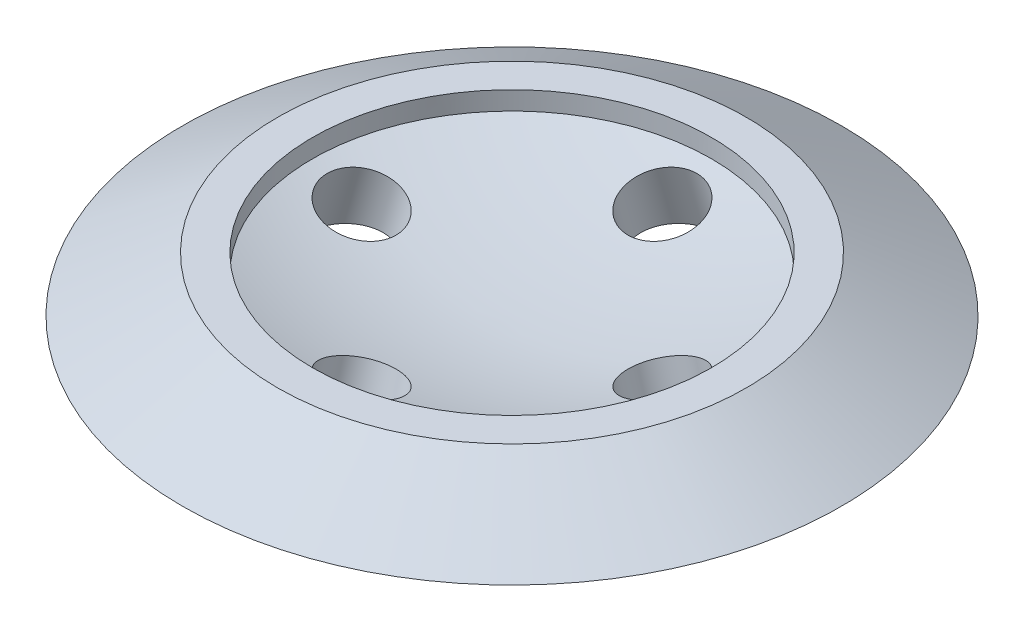
SolidWorks part; units mm, degrees
material "陶瓷"
ref_plane "前视基准面" through (0, 0, 0) normal (0, 0, 1) x (1, 0, 0)
ref_plane "上视基准面" through (0, 0, 0) normal (0, 1, 0) x (1, 0, 0)
ref_plane "右视基准面" through (0, 0, 0) normal (1, 0, 0) x (0, 0, -1)
sketch "草图1" plane through (0, 0, 0) normal (1, 0, 0) x (0, 0, -1)
  line L1 (60, 0) -> (42.6795, 10)
  line L2 (42.6795, 10) -> (36.3261, 10)
  line L12 (0, 23.8695) -> (0, -5.0858) construction
  line L24 (36.3261, 10) -> (36.3261, 6.6322)
  line L25 (0, 0) -> (0, -5.0858)
  line L26 (60, 0) -> (54, 0)
  line L27 (45.1911, -5.0858) -> (0, -5.0858)
  line L29 (54, 0) -> (45.1911, -5.0858)
  arc A1 (0, 0) -> (36.3261, 6.6322) centre (0, 102.8) ccw
  dimension "D11" = 205.6
  dimension "D1" = 60
  dimension "D2" = 10
  dimension "D4" = 6
  dimension "D6" = 30
  dimension "D12" = 150
revolve "旋转1" add sketch "草图1" angle 360 about L12
sketch "草图2" plane through (0, 0, 0) normal (0, 0, 1) x (1, 0, 0)
  line L0 (0, 46.7552) -> (0, -37.8066) construction
  line L1 (0, 99.4096) -> (37.1387, -30.1084) construction
  line L2 (23.1166, 18.7925) -> (29.3648, 20.5841)
  line L3 (29.3648, 20.5841) -> (39.5641, -14.985)
  line L4 (39.5641, -14.985) -> (33.3159, -16.7767)
  line L7 (23.1166, 18.7925) -> (33.3159, -16.7767)
  line L8 (0, 89.2705) -> (0, -48.8197) construction
  circle A0 centre (0, 99.4096) radius 96.5073 construction
  dimension "D1" = 16
  dimension "D3" = 6.5
revolve "切除-旋转1" cut sketch "草图2" angle 360 about L1
pattern_circular "阵列(圆周)1" count 4 over 360 about axis through (0, 6.6322, 0) along (0, 1, 0) of "切除-旋转1"
